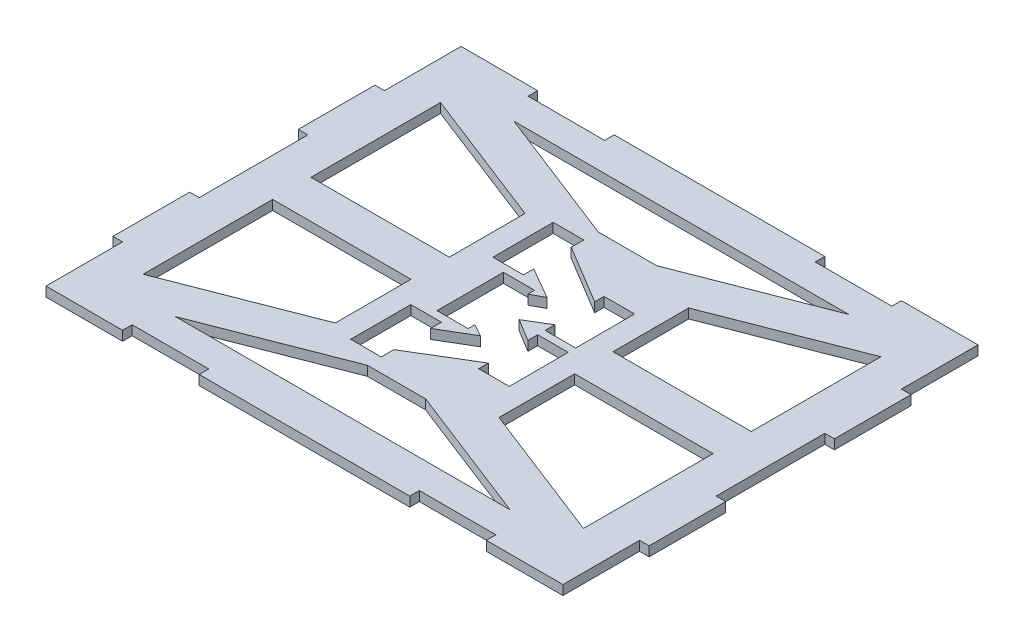
SolidWorks part; units mm, degrees
ref_plane "Front Plane" through (0, 0, 0) normal (0, 0, 1) x (1, 0, 0)
ref_plane "Top Plane" through (0, 0, 0) normal (0, 1, 0) x (1, 0, 0)
ref_plane "Right Plane" through (0, 0, 0) normal (1, 0, 0) x (0, 0, -1)
sketch "Sketch1" plane through (0, 0, 0) normal (0, 1, 0) x (1, 0, 0)
  line L0 (-88.9, 68.834) -> (-88.9, -68.834) construction
  line L1 (-85.725, 68.834) -> (-60.325, 68.834)
  line L2 (-85.725, 68.834) -> (-85.725, 43.434)
  line L3 (-85.725, -68.834) -> (-60.325, -68.834)
  line L4 (85.725, 68.834) -> (85.725, 43.434)
  line L5 (88.9, 68.834) -> (88.9, -68.834) construction
  line L6 (-85.725, 65.659) -> (85.725, 65.659) construction
  line L7 (-85.725, -65.659) -> (85.725, -65.659) construction
  line L8 (-85.725, 43.434) -> (-88.9, 43.434)
  line L9 (-88.9, 43.434) -> (-88.9, 18.034)
  line L10 (-88.9, 18.034) -> (-85.725, 18.034)
  line L11 (-85.725, -18.034) -> (-88.9, -18.034)
  line L12 (-88.9, -18.034) -> (-88.9, -43.434)
  line L13 (-88.9, -43.434) -> (-85.725, -43.434)
  line L14 (85.725, 43.434) -> (88.9, 43.434)
  line L15 (88.9, 43.434) -> (88.9, 18.034)
  line L16 (88.9, 18.034) -> (85.725, 18.034)
  line L17 (85.725, -43.434) -> (88.9, -43.434)
  line L18 (88.9, -43.434) -> (88.9, -18.034)
  line L19 (88.9, -18.034) -> (85.725, -18.034)
  line L20 (-60.325, 68.834) -> (-60.325, 65.659)
  line L21 (-60.325, 65.659) -> (-34.925, 65.659)
  line L22 (-34.925, 65.659) -> (-34.925, 68.834)
  line L23 (34.925, 68.834) -> (34.925, 65.659)
  line L24 (34.925, 65.659) -> (60.325, 65.659)
  line L25 (60.325, 65.659) -> (60.325, 68.834)
  line L26 (-60.325, -68.834) -> (-60.325, -65.659)
  line L27 (-60.325, -65.659) -> (-34.925, -65.659)
  line L28 (-34.925, -65.659) -> (-34.925, -68.834)
  line L29 (34.925, -68.834) -> (34.925, -65.659)
  line L30 (34.925, -65.659) -> (60.325, -65.659)
  line L31 (60.325, -65.659) -> (60.325, -68.834)
  line L32 (486.3142, -205.4935) -> (486.3142, -1570.8269) construction
  line L33 (504, -302.3333) -> (504, -1667.6667) construction
  line L34 (-9.775, 16.9936) -> (0.6066, 10.9841)
  line L35 (-9.6413, 38.2836) -> (9.6413, 38.2836)
  line L36 (-27.1519, 31.4698) -> (-27.1519, 6.35)
  line L37 (-9.6413, -38.2836) -> (9.6413, -38.2836)
  line L38 (27.1519, 31.4698) -> (27.1519, 6.35)
  line L39 (-19.9168, 33.5726) -> (-9.775, 33.5726)
  line L40 (-19.9168, 33.5726) -> (-19.9168, 13.5657)
  line L41 (-19.9168, 13.5657) -> (-9.775, 13.5657)
  line L42 (-9.775, 33.5726) -> (-9.775, 29.4232)
  line L43 (-13.8317, 10.9841) -> (-3.5055, 10.9841)
  line L44 (-13.8317, 10.9841) -> (-13.8317, -11.0512)
  line L45 (-13.8317, -11.0512) -> (-3.5055, -11.0512)
  line L46 (-3.5055, 10.9841) -> (-3.5055, 8.762)
  line L47 (9.7709, 20.7571) -> (19.9127, 20.7571)
  line L48 (9.7709, 20.7571) -> (9.7709, 17.6545)
  line L49 (9.7709, 1.2112) -> (19.9127, 1.2112)
  line L50 (19.9127, 20.7571) -> (19.9127, 1.2112)
  line L51 (9.7709, -1.2782) -> (19.9127, -1.2782)
  line L52 (9.7709, -1.2782) -> (9.7709, -4.5106)
  line L53 (9.7709, -20.8241) -> (19.9127, -20.8241)
  line L54 (19.9127, -1.2782) -> (19.9127, -20.8241)
  line L55 (-19.9168, -13.6461) -> (-9.775, -13.6461)
  line L56 (-19.9168, -13.6461) -> (-19.9168, -33.5848)
  line L57 (-19.9168, -33.5848) -> (-9.775, -33.5848)
  line L58 (-9.775, -13.6461) -> (-9.775, -17.2131)
  line L59 (0.6066, 10.9841) -> (-3.5055, 8.762)
  line L60 (-9.775, -17.2131) -> (0.6066, -11.0512)
  line L61 (0.6066, -11.0512) -> (-3.5055, -8.7986)
  line L62 (-9.775, 29.4232) -> (9.7709, 17.6545)
  line L63 (-9.775, -29.405) -> (9.7709, -17.5826)
  line L64 (2.3664, 0) -> (9.7709, -4.5106)
  line L65 (2.3664, 0) -> (9.7709, 4.412)
  line L66 (-9.775, 16.9936) -> (-9.775, 13.5657)
  line L67 (9.7709, 4.412) -> (9.7709, 1.2112)
  line L68 (-3.5055, -8.7986) -> (-3.5055, -11.0512)
  line L69 (9.7709, -17.5826) -> (9.7709, -20.8241)
  line L70 (-9.775, -29.405) -> (-9.775, -33.5848)
  line L71 (-73.025, 56.134) -> (-27.1519, 38.2836) construction
  line L72 (-55.5144, 56.134) -> (55.5144, 56.134)
  line L73 (-73.025, 49.3202) -> (-73.025, 6.35)
  line L74 (-55.5144, -56.134) -> (73.025, -56.134)
  line L75 (73.025, 49.3202) -> (73.025, 6.35)
  line L76 (27.1519, 38.2836) -> (73.025, 56.134) construction
  line L77 (27.1519, -38.2836) -> (73.025, -56.134) construction
  line L78 (-73.025, -56.134) -> (-27.1519, -38.2836) construction
  line L79 (-55.5144, -56.134) -> (-9.6413, -38.2836)
  line L80 (-73.025, -49.3202) -> (-27.1519, -31.4698)
  line L81 (-73.025, 49.3202) -> (-27.1519, 31.4698)
  line L82 (-55.5144, 56.134) -> (-9.6413, 38.2836)
  line L83 (9.6413, 38.2836) -> (55.5144, 56.134)
  line L84 (27.1519, 31.4698) -> (73.025, 49.3202)
  line L85 (9.6413, -38.2836) -> (55.5144, -56.134)
  line L86 (27.1519, -31.4698) -> (73.025, -49.3202)
  line L87 (-85.725, 0) -> (85.725, 0) construction
  line L88 (-34.925, 68.834) -> (34.925, 68.834)
  line L89 (-73.025, 6.35) -> (-27.1519, 6.35)
  line L91 (-73.025, -6.35) -> (-27.1519, -6.35)
  line L92 (-73.025, -6.35) -> (-73.025, -49.3202)
  line L93 (27.1519, 6.35) -> (73.025, 6.35)
  line L94 (-27.1519, -6.35) -> (-27.1519, -31.4698)
  line L95 (27.1519, -6.35) -> (73.025, -6.35)
  line L96 (27.1519, -6.35) -> (27.1519, -31.4698)
  line L97 (-85.725, 18.034) -> (-85.725, -18.034)
  line L98 (60.325, 68.834) -> (85.725, 68.834)
  line L99 (85.725, 18.034) -> (85.725, -18.034)
  line L100 (85.725, -43.434) -> (85.725, -68.834)
  line L101 (60.325, -68.834) -> (85.725, -68.834)
  line L102 (-34.925, -68.834) -> (34.925, -68.834)
  line L103 (-85.725, -43.434) -> (-85.725, -68.834)
  line L104 (73.025, -6.35) -> (73.025, -56.134)
  dimension "D1" = 137.668
  dimension "D2" = 171.45
  dimension "D3" = 3.175
  dimension "D4" = 3.175
  dimension "D5" = 3.175
  dimension "D6" = 3.175
  dimension "D7" = 25.4
  dimension "D8" = 25.4
  dimension "D9" = 25.4
  dimension "D10" = 25.4
  dimension "D11" = 25.4
  dimension "D12" = 25.4
  dimension "D13" = 25.4
  dimension "D14" = 25.4
  dimension "D15" = 25.4
  dimension "D16" = 25.4
  dimension "D17" = 25.4
  dimension "D18" = 25.4
  dimension "D19" = 25.4
  dimension "D20" = 25.4
  dimension "D21" = 25.4
  dimension "D22" = 25.4
  dimension "D23" = 12.7
  dimension "D24" = 12.7
  dimension "D25" = 6.35
  dimension "D26" = 6.35
  dimension "D27" = 6.35
  dimension "D28" = 6.35
  dimension "D29" = 6.35
  dimension "D30" = 6.35
  dimension "D31" = 6.35
  dimension "D32" = 6.35
  dimension "D33" = 12.7
  dimension "D34" = 6.35
  dimension "D35" = 12.7
  dimension "D36" = 6.35
extrude "Boss-Extrude1" add sketch "Sketch1" along normal blind 3.175 contours L13 L103 L3 L26 L27 L28 L102 L29 L30 L31 L101 L100 L17 L18 L19 L99 L16 L15 L14 L4 L98 L25 L24 L23 L88 L22 L21 L20 L1 L2 L8 L9 L10 L97 L11 L12 L91 L94 L80 L92 L63 L70 L57 L56 L55 L58 L60 L61 L68
